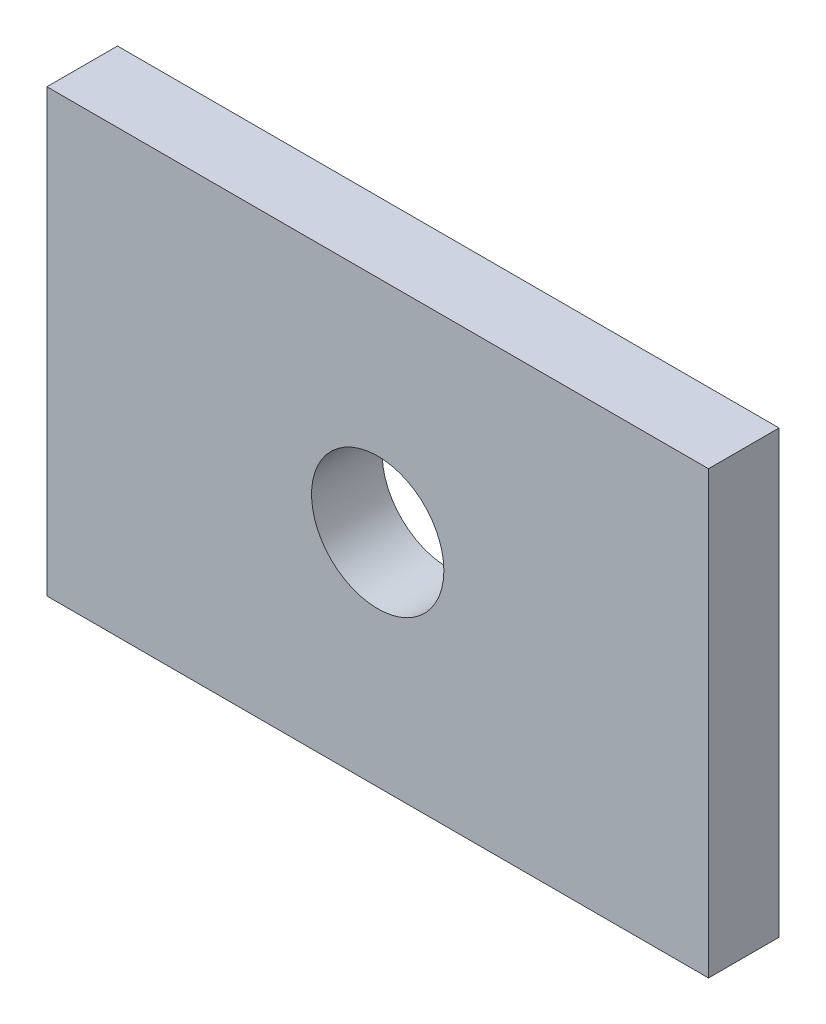
SolidWorks part; units mm, degrees
material "Q235A"
ref_plane "前视" through (0, 0, 0) normal (0, 0, 1) x (1, 0, 0)
ref_plane "上视" through (0, 0, 0) normal (0, 1, 0) x (1, 0, 0)
ref_plane "右视" through (0, 0, 0) normal (1, 0, 0) x (0, 0, -1)
sketch "草图1" plane through (0, 0, 0) normal (0, 0, 1) x (1, 0, 0)
  line L1 (75, -50) -> (-75, -50)
  line L2 (75, -50) -> (75, 50)
  line L3 (75, 50) -> (-75, 50)
  line L4 (-75, -50) -> (-75, 50)
  line L5 (75, -50) -> (-75, 50) construction
  line L6 (75, 50) -> (-75, -50) construction
  point P0 (0, 0)
  dimension "D1" = 100
  dimension "D2" = 150
extrude "凸台-拉伸1" add sketch "草图1" along normal blind 16
hole_wizard "Ø6.0 (6) 直径孔1" positions "草图3" profile "草图2" hole size "Ø6.0" standard "GB"
sketch "草图3" plane through (0, 0, 16) normal (0, 0, 1) x (1, 0, 0)
  point P0 (0, 0)
sketch "草图2" plane through (0, 0, 16) normal (1, 0, 0) x (0, -1, 0)
  line L0 (0, 0) -> (0, 29.0129)
  line L1 (0, 29.0129) -> (15, 20)
  line L2 (15, 20) -> (15, 0)
  line L5 (15, 0) -> (0, 0)
  line L10 (0, 29.0129) -> (-15, 20) construction
  line L11 (0, -6.35) -> (0, 107.95) construction
  dimension "孔直径" = 30
  dimension "孔深度" = 20
  dimension "导头角度" = 118
